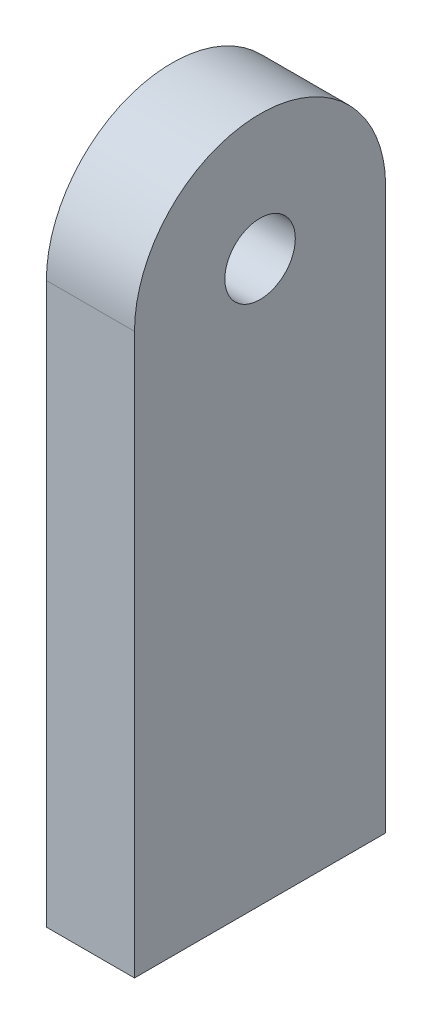
SolidWorks part; units mm, degrees
ref_plane "Спереди" through (0, 0, 0) normal (0, 0, 1) x (1, 0, 0)
ref_plane "Сверху" through (0, 0, 0) normal (0, 1, 0) x (1, 0, 0)
ref_plane "Справа" through (0, 0, 0) normal (1, 0, 0) x (0, 0, -1)
sketch "Эскиз1" plane through (0, 0, 0) normal (1, 0, 0) x (0, 0, -1)
  line L2 (21.5, -78.7374) -> (50, -78.7374)
  line L3 (50, -15) -> (50, -78.7374)
  line L4 (21.5, -15.186) -> (21.5, -78.7374)
  line L14 (35.75, -78.7374) -> (35.75, -37.3357) construction
  arc A0 (21.5, -15.186) -> (50, -15) centre (35.7506, -15.186) cw
  circle A3 centre (35.75, -15.186) radius 4
extrude "Вытянуть1" add sketch "Эскиз1" along normal blind 10
